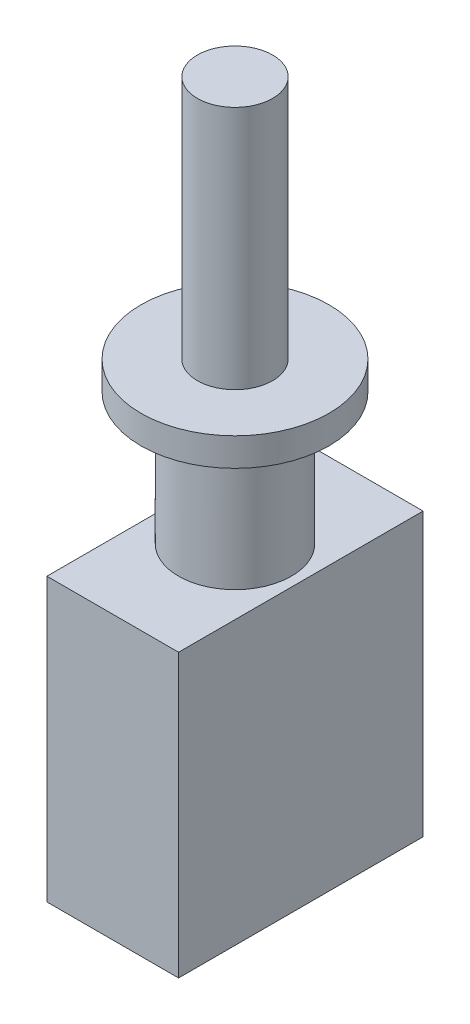
SolidWorks part; units mm, degrees
material "ABS"
ref_plane "Plan de face" through (0, 0, 0) normal (0, 0, 1) x (1, 0, 0)
ref_plane "Plan de dessus" through (0, 0, 0) normal (0, 1, 0) x (1, 0, 0)
ref_plane "Plan de droite" through (0, 0, 0) normal (1, 0, 0) x (0, 0, -1)
sketch "Esquisse1" plane through (0, 0, 0) normal (0, 1, 0) x (1, 0, 0)
  line L0 (-3.5, -6.5) -> (3.5, 6.5) construction
  line L1 (-3.5, -6.5) -> (3.5, -6.5)
  line L2 (-3.5, -6.5) -> (-3.5, 6.5)
  line L3 (-3.5, 6.5) -> (3.5, 6.5)
  line L4 (3.5, -6.5) -> (3.5, 6.5)
  dimension "D1" = 7
  dimension "D2" = 13
extrude "Extrusion1" add sketch "Esquisse1" along normal blind 15
sketch "Esquisse2" plane through (0, 15, 0) normal (0, 1, 0) x (-1, 0, 0)
  line L0 (3.5, 0) -> (-3.5, 0) construction
  line L1 (3.5, -6.5) -> (3.5, 6.5) construction
  line L2 (-3.5, 6.5) -> (-3.5, -6.5) construction
  circle A0 centre (0, 0) radius 3
  dimension "D1" = 6
extrude "Extrusion2" add sketch "Esquisse2" along normal blind 7
sketch "Esquisse3" plane through (0, 22, 0) normal (0, 1, 0) x (-1, 0, 0)
  circle A0 centre (0, 0) radius 5
  circle A1 centre (0, 0) radius 3 construction
  dimension "D1" = 10
extrude "Extrusion3" add sketch "Esquisse3" along normal blind 1.5
sketch "Esquisse4" plane through (0, 23.5, 0) normal (0, 1, 0) x (-1, 0, 0)
  circle A0 centre (0, 0) radius 2
  circle A1 centre (0, 0) radius 5 construction
  dimension "D1" = 4
extrude "Extrusion4" add sketch "Esquisse4" along normal blind 13
